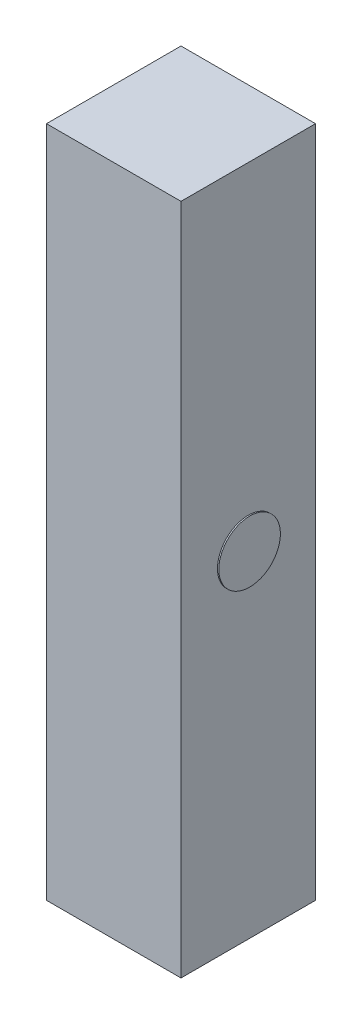
SolidWorks part; units mm, degrees
ref_plane "Front Plane" through (0, 0, 0) normal (0, 0, 1) x (1, 0, 0)
ref_plane "Top Plane" through (0, 0, 0) normal (0, 1, 0) x (1, 0, 0)
ref_plane "Right Plane" through (0, 0, 0) normal (1, 0, 0) x (0, 0, -1)
sketch "Sketch1" plane through (0, 0, 0) normal (0, 0, 1) x (1, 0, 0)
  line L1 (0, 0) -> (1, 0)
  line L2 (0, 0) -> (0, -5)
  line L3 (0, -5) -> (1, -5)
  line L4 (1, 0) -> (1, -5)
  dimension "D1" = 1
  dimension "D2" = 5
extrude "Boss-Extrude1" add sketch "Sketch1" along normal blind 1
sketch "Sketch2" plane through (1, 0, 0) normal (1, 0, 0) x (0, 0, -1)
  line L0 (-1, 0) -> (0, -5)
  circle A0 centre (-0.5, -2.5) radius 0.2289
extrude "Boss-Extrude2" add sketch "Sketch2" along normal blind 0.01 contours A0
